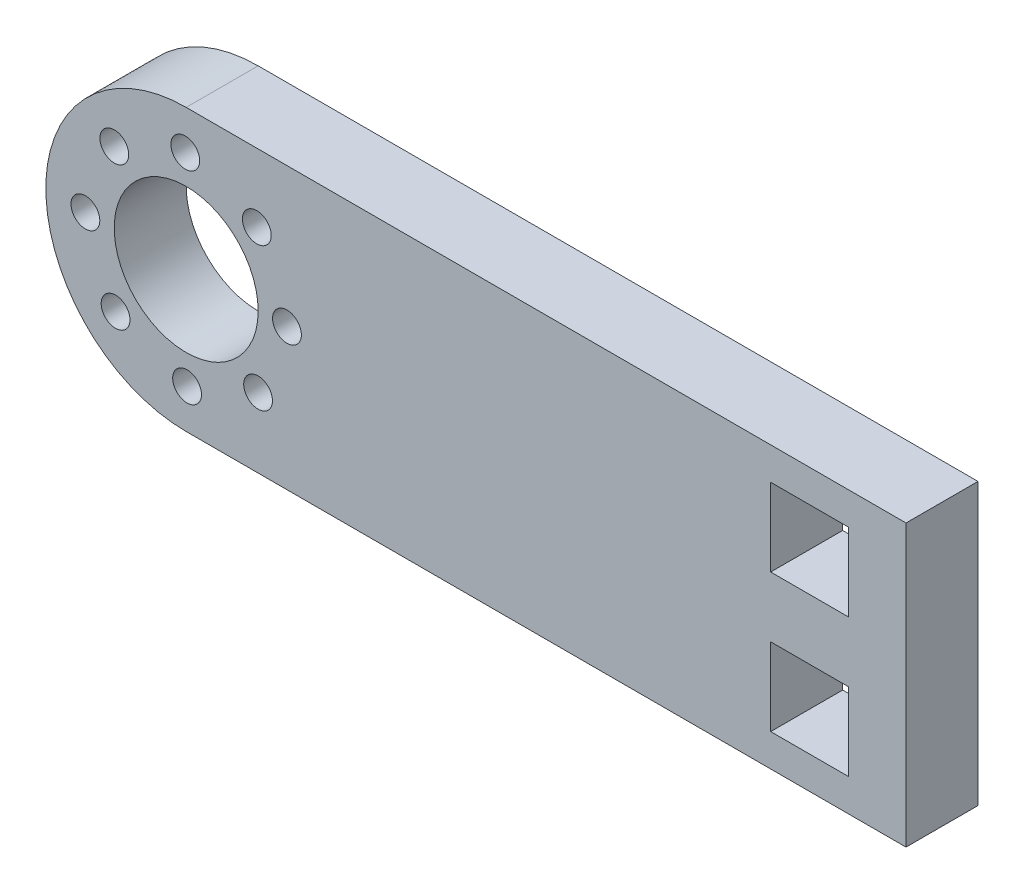
SolidWorks part; units mm, degrees
ref_plane "Front Plane" through (0, 0, 0) normal (0, 0, 1) x (1, 0, 0)
ref_plane "Top Plane" through (0, 0, 0) normal (0, 1, 0) x (1, 0, 0)
ref_plane "Right Plane" through (0, 0, 0) normal (1, 0, 0) x (0, 0, -1)
sketch "Sketch2" plane through (0, 0, 0) normal (0, 0, 1) x (1, 0, 0)
  line L0 (-5.7491, 12.0423) -> (44.2509, 12.0423)
  line L1 (44.2509, 12.0423) -> (44.2509, -7.4577)
  line L2 (44.2509, -7.4577) -> (-5.7491, -7.4577)
  line L17 (34.8509, 9.7923) -> (40.2509, 9.7923)
  line L18 (34.8509, 9.7923) -> (34.8509, 4.3923)
  line L19 (34.8509, 4.3923) -> (40.2509, 4.3923)
  line L20 (40.2509, 9.7923) -> (40.2509, 4.3923)
  line L21 (34.8509, 0.1923) -> (40.2509, 0.1923)
  line L22 (34.8509, 0.1923) -> (34.8509, -5.2077)
  line L23 (34.8509, -5.2077) -> (40.2509, -5.2077)
  line L24 (40.2509, 0.1923) -> (40.2509, -5.2077)
  arc A0 (-5.7491, 12.0423) -> (-5.7491, -7.4577) centre (-5.7491, 2.2923) ccw
  circle A1 centre (-5.8115, 9.2923) radius 1
  circle A2 centre (-10.7428, 7.1977) radius 1
  circle A3 centre (-12.7491, 2.2298) radius 1
  circle A9 centre (-0.8437, 7.286) radius 1
  circle A10 centre (1.2509, 2.3547) radius 1
  circle A11 centre (-0.7554, -2.6131) radius 1
  circle A12 centre (-5.6866, -4.7077) radius 1
  circle A13 centre (-10.6545, -2.7014) radius 1
  circle A14 centre (-5.7491, 2.2923) radius 5
  dimension "D1" = 10
  dimension "D2" = 2
  dimension "D4" = 2
  dimension "D6" = 2
  dimension "D7" = 2
  dimension "D8" = 2
  dimension "D9" = 2
  dimension "D10" = 2
  dimension "D11" = 2
  dimension "D12" = 9.75
  dimension "D3" = 5.4
  dimension "D5" = 5.4
  dimension "D13" = 1.2509
  dimension "D14" = 4
  dimension "D15" = 0.7554
  dimension "D16" = 0.8437
  dimension "D17" = 5.6866
  dimension "D18" = 5.7491
  dimension "D19" = 5.8115
  dimension "D20" = 10.6545
  dimension "D21" = 10.7428
  dimension "D22" = 12.7491
  dimension "D23" = 0.1923
  dimension "D24" = 2.2298
  dimension "D25" = 2.2923
  dimension "D26" = 2.3547
  dimension "D27" = 4.3923
  dimension "D28" = 7.1977
  dimension "D29" = 7.286
  dimension "D30" = 9.2923
  dimension "D31" = 2.6131
  dimension "D32" = 2.7014
  dimension "D33" = 4.7077
  dimension "D34" = 50
extrude "Boss-Extrude1" add sketch "Sketch2" along normal blind 5
